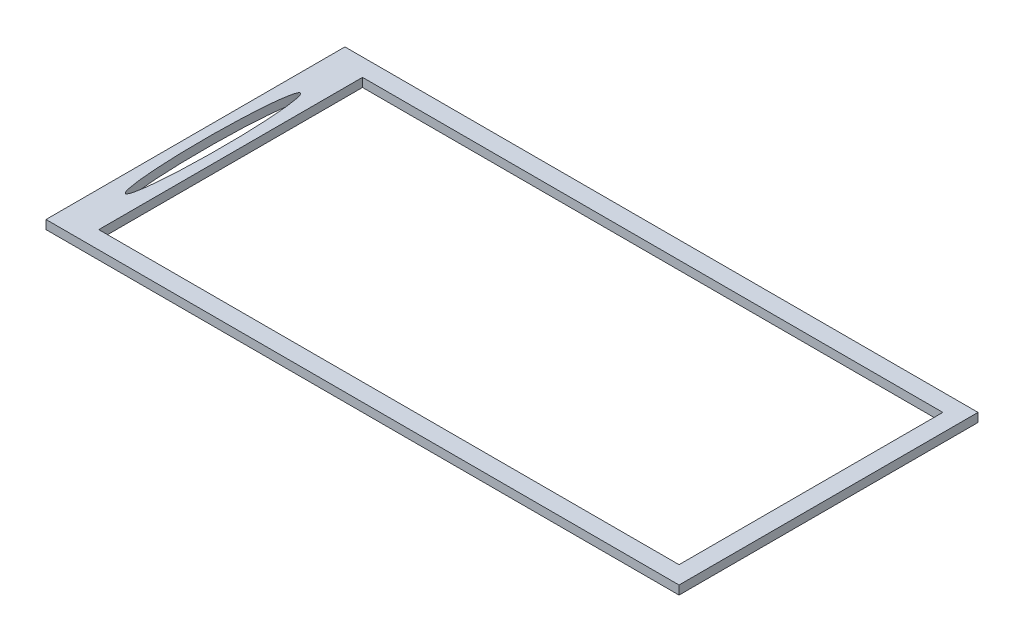
SolidWorks part; units mm, degrees
ref_plane "Alzado" through (0, 0, 0) normal (0, 0, 1) x (1, 0, 0)
ref_plane "Planta" through (0, 0, 0) normal (0, 1, 0) x (1, 0, 0)
ref_plane "Vista lateral" through (0, 0, 0) normal (1, 0, 0) x (0, 0, -1)
sketch "Croquis1" plane through (0, 0, 0) normal (0, 1, 0) x (1, 0, 0)
  line L1 (-360, -170) -> (360, -170)
  line L2 (-360, -170) -> (-360, 170)
  line L3 (-360, 170) -> (360, 170)
  line L4 (360, -170) -> (360, 170)
  line L5 (-360, -170) -> (360, 170) construction
  line L6 (-360, 170) -> (360, -170) construction
  point P0 (0, 0)
  dimension "D1" = 720
  dimension "D2" = 340
extrude "Saliente-Extruir1" add sketch "Croquis1" along normal blind 10
sketch "Croquis3" plane through (0, 10, 0) normal (0, 1, 0) x (1, 0, 0)
  line L0 (360, 170) -> (-360, 170) construction
  line L1 (340, 150) -> (-320, 150)
  line L2 (340, 150) -> (340, -150)
  line L3 (340, -150) -> (-320, -150)
  line L4 (-320, 150) -> (-320, -150)
  line L5 (-360, -170) -> (360, -170) construction
  line L6 (360, -170) -> (360, 170) construction
  ellipse E0 centre (-340.0899, 0) end of major axis (-340.0899, 99.3332) minor radius 8.9793
  dimension "D1" = 20
  dimension "D2" = 20
  dimension "D3" = 20
  dimension "D4" = 680
extrude "Cortar-Extruir2" cut sketch "Croquis3" against normal up to surface (10 mm away) up to face at (0, 0, 0)
